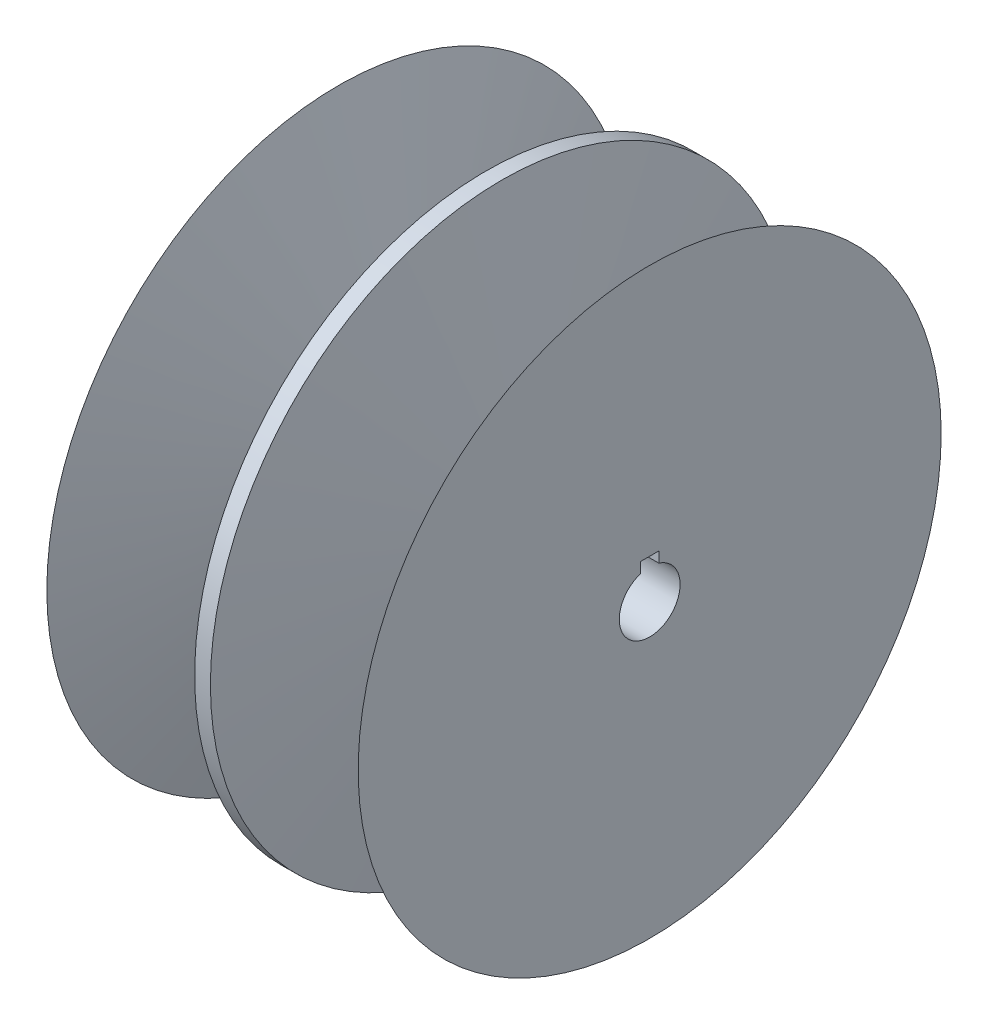
SolidWorks part; units mm, degrees
material "Plain Carbon Steel"
ref_plane "Front Plane" through (0, 0, 0) normal (0, 0, 1) x (1, 0, 0)
ref_plane "Top Plane" through (0, 0, 0) normal (0, 1, 0) x (1, 0, 0)
ref_plane "Right Plane" through (0, 0, 0) normal (1, 0, 0) x (0, 0, -1)
sketch "Sketch1" plane through (0, 0, 0) normal (0, 0, 1) x (1, 0, 0)
  line L0 (0, 0) -> (40.64, 0) construction
  line L1 (0, 0) -> (-40.64, 0) construction
  line L2 (40.64, 0) -> (40.64, 76.0921) construction
  line L3 (0, 0) -> (0, 76.0921) construction
  line L4 (-2.0574, 76.0921) -> (2.0574, 76.0921) construction
  line L5 (40.64, 6.35) -> (-40.64, 6.35) construction
  line L6 (22.0133, 12.7) -> (22.0133, 6.35)
  line L7 (40.64, 76.0921) -> (22.0133, 12.7)
  line L8 (22.0133, 12.7) -> (9.3133, 12.7) construction
  line L9 (9.3133, 12.7) -> (2.0574, 76.0921)
  line L10 (9.3133, 12.7) -> (-9.3133, 12.7) construction
  line L11 (22.0133, 12.7) -> (40.64, 12.7) construction
  line L12 (22.0133, 6.35) -> (40.64, 6.35)
  line L13 (40.64, 6.35) -> (40.64, 76.0921)
  line L14 (9.3133, 12.7) -> (9.3133, 6.35)
  line L15 (9.3133, 6.35) -> (-9.3133, 6.35)
  line L16 (2.0574, 76.0921) -> (-2.0574, 76.0921)
  line L17 (-22.0133, 12.7) -> (-40.64, 12.7) construction
  line L18 (-9.3133, 12.7) -> (-9.3133, 6.35)
  line L19 (-40.64, 6.35) -> (-40.64, 76.0921)
  line L20 (-22.0133, 6.35) -> (-40.64, 6.35)
  line L21 (-9.3133, 12.7) -> (-2.0574, 76.0921)
  line L22 (-22.0133, 12.7) -> (-9.3133, 12.7)
  line L23 (-40.64, 76.0921) -> (-22.0133, 12.7)
  line L24 (-22.0133, 12.7) -> (-22.0133, 6.35)
  point P18 (0, 12.7)
  point P21 (0, 6.35)
  dimension "D1" = 40.64
  dimension "D2" = 40.64
  dimension "D3" = 76.0921
  dimension "D4" = 2.0574
  dimension "D5" = 6.35
  dimension "D7" = 12.7
revolve "Revolve1" add sketch "Sketch1" angle 360 about L1
sketch "Sketch2" plane through (40.64, 0, 0) normal (1, 0, 0) x (0, 0, -1)
  line L0 (0, 0) -> (0, 7.9375) construction
  line L2 (2.3812, 5.5563) -> (-2.3813, 5.5562)
  line L3 (2.3812, 5.5563) -> (2.3812, 10.3188)
  line L4 (2.3812, 10.3188) -> (-2.3813, 10.3188)
  line L5 (-2.3813, 5.5562) -> (-2.3813, 10.3188)
  line L6 (2.3812, 5.5563) -> (-2.3813, 10.3188) construction
  line L7 (2.3812, 10.3188) -> (-2.3813, 5.5562) construction
  circle A0 centre (0, 0) radius 7.9375
  circle M2 centre (0, 0) radius 6.35
  dimension "D1" = 15.875
  dimension "D2" = 4.7625
  dimension "D3" = 4.7625
extrude "Cut-Extrude1" cut sketch "Sketch2" against normal blind 108.204 contours L5 A0 L3 M2 | L3 A0 L5 M2 | A0 L3 L4 L5 | L5 L2 L3 M2
ref_plane "Plane1" through (-15.6633, 0, 0) normal (1, 0, 0) x (0, 0, -1)
ref_plane "Plane2" through (15.6633, 0, 0) normal (-1, 0, 0) x (0, 0, 1)
